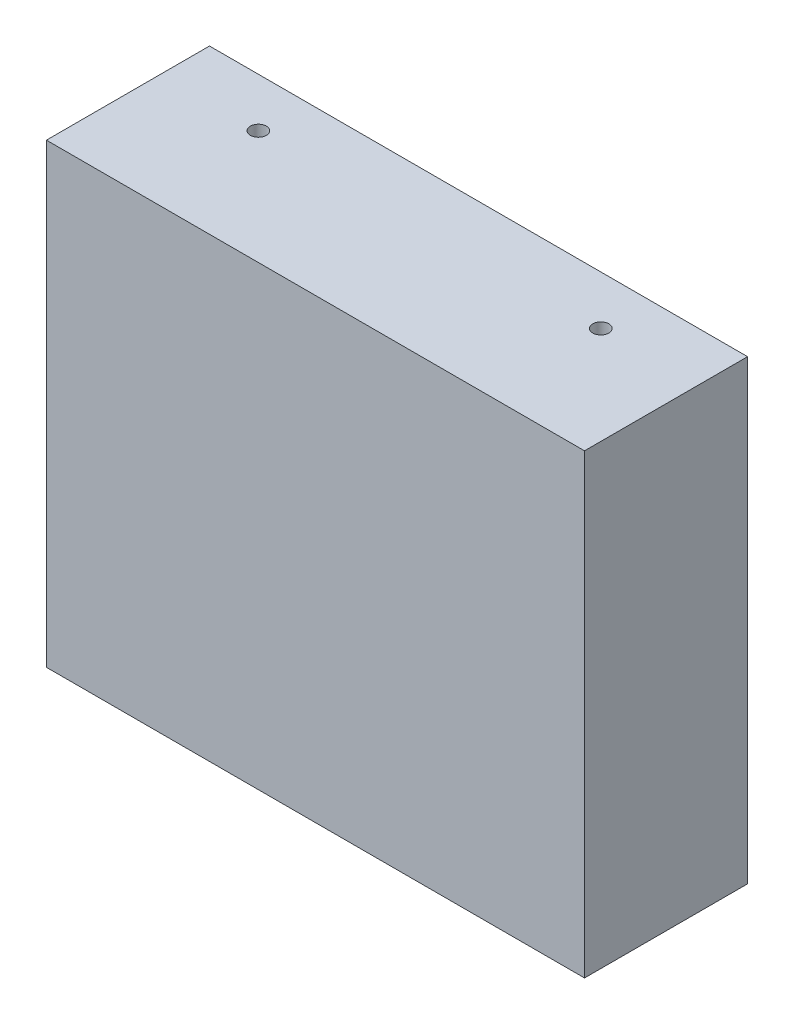
SolidWorks part; units mm, degrees
ref_plane "Front Plane" through (0, 0, 0) normal (0, 0, 1) x (1, 0, 0)
ref_plane "Top Plane" through (0, 0, 0) normal (0, 1, 0) x (1, 0, 0)
ref_plane "Right Plane" through (0, 0, 0) normal (1, 0, 0) x (0, 0, -1)
sketch "Sketch1" plane through (0, 0, 0) normal (0, 0, 1) x (1, 0, 0)
  line L1 (419.1, -355.6) -> (-419.1, -355.6)
  line L2 (419.1, -355.6) -> (419.1, 355.6)
  line L3 (419.1, 355.6) -> (-419.1, 355.6)
  line L4 (-419.1, -355.6) -> (-419.1, 355.6)
  line L5 (419.1, -355.6) -> (-419.1, 355.6) construction
  line L6 (419.1, 355.6) -> (-419.1, -355.6) construction
  point P0 (0, 0)
  dimension "D1" = 838.2
  dimension "D2" = 711.2
extrude "Boss-Extrude1" add sketch "Sketch1" along normal blind 254
hole_wizard "Ø25.0mm Dowel Hole1" positions "Sketch2" profile "Sketch3" hole size "Ø25.0" standard "DIN" end condition through all
sketch "Sketch2" plane through (0, -355.6, 0) normal (0, -1, 0) x (-1, 0, 0)
  line L0 (419.1, -76.2) -> (-419.1, -76.2) construction
  line L1 (419.1, -254) -> (419.1, 0) construction
  line L2 (-419.1, -254) -> (-419.1, 0) construction
  line L4 (419.1, 0) -> (-419.1, 0) construction
  point P0 (266.7, -76.2)
  point P2 (-266.7, -76.2)
  point P14 (0, 0)
  point P15 (0, 0)
  dimension "D1" = 76.2
  dimension "D2" = 152.4
  dimension "D3" = 152.4
sketch "Sketch3" plane through (-266.7, -355.6, 76.2) normal (1, 0, 0) x (0, 0, -1)
  line L0 (0, 0) -> (0, 711.2)
  line L1 (0, 711.2) -> (12.5, 711.2)
  line L2 (12.5, 711.2) -> (12.5, 0)
  line L5 (12.5, 0) -> (0, 0)
  line L11 (0, -6.35) -> (0, 107.95) construction
  dimension "Thru Hole Dia." = 25
  dimension "Thru Hole Depth" = 711.2
